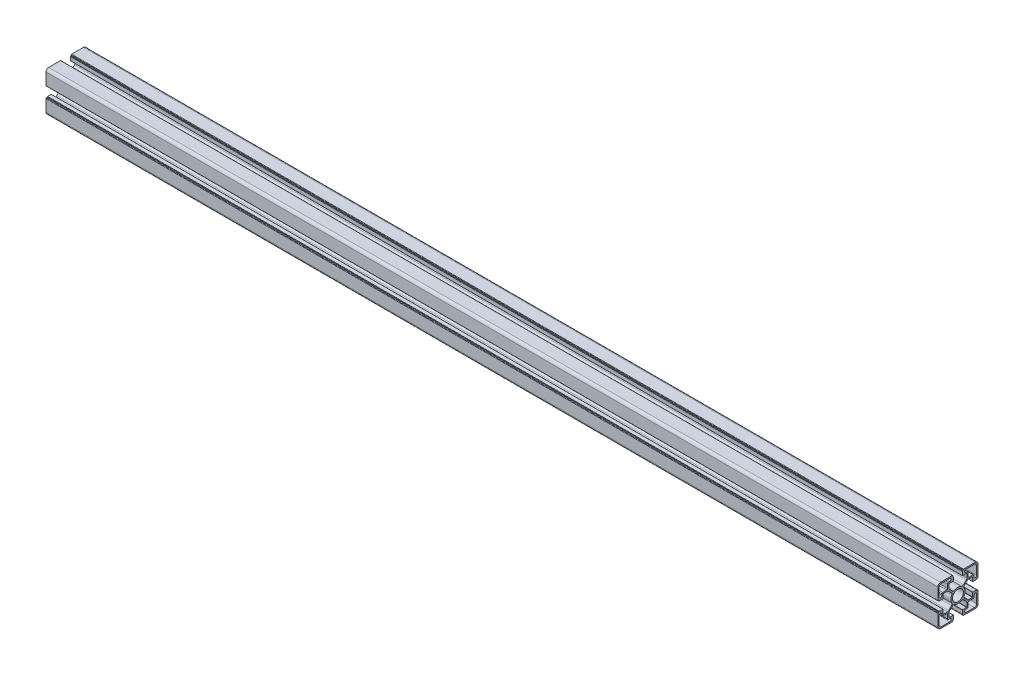
SolidWorks part; units mm, degrees
material "6061 Alloy"
ref_plane "Front Plane" through (0, 0, 0) normal (0, 0, 1) x (1, 0, 0)
ref_plane "Top Plane" through (0, 0, 0) normal (0, 1, 0) x (1, 0, 0)
ref_plane "Right Plane" through (0, 0, 0) normal (1, 0, 0) x (0, 0, -1)
sketch "Sketch1" plane through (0, 0, 0) normal (1, 0, 0) x (0, 0, -1)
  line L0 (0, 0) -> (-22.3216, 22.3216) construction
  line L1 (0, 0) -> (-31.5011, 0) construction
  line L2 (-22.5, 19.5) -> (-22.5, 6.3)
  line L3 (-20.7, 5) -> (-16.7, 5)
  line L4 (-16.5, 5.2) -> (-16.5, 9.8)
  line L5 (-16.3, 10) -> (-11.8642, 10)
  line L6 (-10.4924, 9.4318) -> (-7.2967, 6.236)
  line L7 (-21, 18.5) -> (-21, 9)
  line L8 (-16.5, 5) -> (-16.5, 10) construction
  line L9 (-18, 9) -> (-18, 10.5)
  line L10 (-17, 11.5) -> (-12.5, 11.5)
  line L11 (-22, 5.8) -> (-21.3, 5.8)
  line L12 (-21, 5.5) -> (-21, 5.3)
  line L13 (-21, 22.5) -> (-21, 6.5) construction
  line L14 (-18, 11.5) -> (-10.4393, 11.5) construction
  line L15 (-10.4393, 11.5) -> (-5.1016, 6.1623) construction
  line L16 (-18, 6.5) -> (-18, 11.5) construction
  line L17 (-22.5, 22.5) -> (-22.5, 5) construction
  line L18 (-22.5, 5) -> (-16.5, 5) construction
  line L19 (-21, 6.5) -> (-18, 6.5) construction
  line L20 (-16.5, 10) -> (-11.0607, 10) construction
  line L21 (-11.0607, 10) -> (-6.1623, 5.1016) construction
  line L22 (-5.5, 21) -> (-5.3, 21)
  line L23 (-5.8, 22) -> (-5.8, 21.3)
  line L24 (-11.5, 17) -> (-11.5, 12.5)
  line L25 (-9, 18) -> (-10.5, 18)
  line L26 (-18.5, 21) -> (-9, 21)
  line L27 (-9.4318, 10.4924) -> (-6.236, 7.2967)
  line L28 (-10, 16.3) -> (-10, 11.8642)
  line L29 (-5.2, 16.5) -> (-9.8, 16.5)
  line L30 (-5, 20.7) -> (-5, 16.7)
  line L31 (-19.5, 22.5) -> (-6.3, 22.5)
  line L32 (19.5, 22.5) -> (6.3, 22.5)
  line L33 (5, 20.7) -> (5, 16.7)
  line L34 (5.2, 16.5) -> (9.8, 16.5)
  line L35 (10, 16.3) -> (10, 11.8642)
  line L36 (9.4318, 10.4924) -> (6.236, 7.2967)
  line L37 (18.5, 21) -> (9, 21)
  line L38 (9, 18) -> (10.5, 18)
  line L39 (11.5, 17) -> (11.5, 12.5)
  line L40 (5.8, 22) -> (5.8, 21.3)
  line L41 (5.5, 21) -> (5.3, 21)
  line L42 (21, 5.5) -> (21, 5.3)
  line L43 (22, 5.8) -> (21.3, 5.8)
  line L44 (17, 11.5) -> (12.5, 11.5)
  line L45 (18, 9) -> (18, 10.5)
  line L46 (21, 18.5) -> (21, 9)
  line L47 (10.4924, 9.4318) -> (7.2967, 6.236)
  line L48 (16.3, 10) -> (11.8642, 10)
  line L49 (16.5, 5.2) -> (16.5, 9.8)
  line L50 (20.7, 5) -> (16.7, 5)
  line L51 (22.5, 19.5) -> (22.5, 6.3)
  line L52 (0, 0) -> (22.3216, 22.3216) construction
  line L53 (0, 0) -> (0, 31.5011) construction
  line L54 (22.5, -19.5) -> (22.5, -6.3)
  line L55 (20.7, -5) -> (16.7, -5)
  line L56 (16.5, -5.2) -> (16.5, -9.8)
  line L57 (16.3, -10) -> (11.8642, -10)
  line L58 (10.4924, -9.4318) -> (7.2967, -6.236)
  line L59 (21, -18.5) -> (21, -9)
  line L60 (18, -9) -> (18, -10.5)
  line L61 (17, -11.5) -> (12.5, -11.5)
  line L62 (22, -5.8) -> (21.3, -5.8)
  line L63 (21, -5.5) -> (21, -5.3)
  line L64 (5.5, -21) -> (5.3, -21)
  line L65 (5.8, -22) -> (5.8, -21.3)
  line L66 (11.5, -17) -> (11.5, -12.5)
  line L67 (9, -18) -> (10.5, -18)
  line L68 (18.5, -21) -> (9, -21)
  line L69 (9.4318, -10.4924) -> (6.236, -7.2967)
  line L70 (10, -16.3) -> (10, -11.8642)
  line L71 (5.2, -16.5) -> (9.8, -16.5)
  line L72 (5, -20.7) -> (5, -16.7)
  line L73 (19.5, -22.5) -> (6.3, -22.5)
  line L74 (0, 0) -> (22.3216, -22.3216) construction
  line L75 (0, 0) -> (31.5011, 0) construction
  line L76 (-19.5, -22.5) -> (-6.3, -22.5)
  line L77 (-5, -20.7) -> (-5, -16.7)
  line L78 (-5.2, -16.5) -> (-9.8, -16.5)
  line L79 (-10, -16.3) -> (-10, -11.8642)
  line L80 (-9.4318, -10.4924) -> (-6.236, -7.2967)
  line L81 (-18.5, -21) -> (-9, -21)
  line L82 (-9, -18) -> (-10.5, -18)
  line L83 (-11.5, -17) -> (-11.5, -12.5)
  line L84 (-5.8, -22) -> (-5.8, -21.3)
  line L85 (-5.5, -21) -> (-5.3, -21)
  line L86 (-21, -5.5) -> (-21, -5.3)
  line L87 (-22, -5.8) -> (-21.3, -5.8)
  line L88 (-17, -11.5) -> (-12.5, -11.5)
  line L89 (-18, -9) -> (-18, -10.5)
  line L90 (-21, -18.5) -> (-21, -9)
  line L91 (-10.4924, -9.4318) -> (-7.2967, -6.236)
  line L92 (-16.3, -10) -> (-11.8642, -10)
  line L93 (-16.5, -5.2) -> (-16.5, -9.8)
  line L94 (-20.7, -5) -> (-16.7, -5)
  line L95 (-22.5, -19.5) -> (-22.5, -6.3)
  line L96 (0, 0) -> (-22.3216, -22.3216) construction
  line L97 (0, 0) -> (0, -31.5011) construction
  arc A0 (0, 6.1) -> (-6.1, 0) centre (0, 0) ccw
  arc A1 (-6.9766, 3.9149) -> (-8, 0) centre (0, 0) ccw
  arc A2 (-21, 9) -> (-18, 9) centre (-19.5, 9) ccw
  arc A3 (-22, 5.8) -> (-22.5, 6.3) centre (-22, 6.3) cw
  arc A4 (-21.3, 5.8) -> (-21, 5.5) centre (-21.3, 5.5) cw
  arc A5 (-21, 5.3) -> (-20.7, 5) centre (-20.7, 5.3) ccw
  arc A6 (-16.7, 5) -> (-16.5, 5.2) centre (-16.7, 5.2) ccw
  arc A7 (-16.5, 9.8) -> (-16.3, 10) centre (-16.3, 9.8) cw
  arc A8 (-7.2967, 6.236) -> (-6.9766, 3.9149) centre (-8.6685, 4.8643) cw
  arc A9 (-11.8642, 10) -> (-10.4924, 9.4318) centre (-11.8642, 8.06) cw
  arc A10 (-18, 10.5) -> (-17, 11.5) centre (-17, 10.5) cw
  arc A11 (-10.5, 18) -> (-11.5, 17) centre (-10.5, 17) ccw
  arc A12 (-10, 11.8642) -> (-9.4318, 10.4924) centre (-8.06, 11.8642) ccw
  arc A13 (-6.236, 7.2967) -> (-3.9149, 6.9766) centre (-4.8643, 8.6685) ccw
  arc A14 (-9.8, 16.5) -> (-10, 16.3) centre (-9.8, 16.3) ccw
  arc A15 (-5, 16.7) -> (-5.2, 16.5) centre (-5.2, 16.7) cw
  arc A16 (-5.3, 21) -> (-5, 20.7) centre (-5.3, 20.7) cw
  arc A17 (-5.8, 21.3) -> (-5.5, 21) centre (-5.5, 21.3) ccw
  arc A18 (-5.8, 22) -> (-6.3, 22.5) centre (-6.3, 22) ccw
  arc A19 (-9, 21) -> (-9, 18) centre (-9, 19.5) cw
  arc A20 (-3.9149, 6.9766) -> (0, 8) centre (0, 0) cw
  arc A21 (-12.5, 11.5) -> (-11.5, 12.5) centre (-12.5, 12.5) ccw
  arc A22 (-21, 18.5) -> (-18.5, 21) centre (-18.5, 18.5) cw
  arc A23 (-22.5, 19.5) -> (-19.5, 22.5) centre (-19.5, 19.5) cw
  arc A24 (6.1, 0) -> (0, 6.1) centre (0, 0) ccw
  arc A25 (3.9149, 6.9766) -> (0, 8) centre (0, 0) ccw
  arc A26 (9, 21) -> (9, 18) centre (9, 19.5) ccw
  arc A27 (5.8, 22) -> (6.3, 22.5) centre (6.3, 22) cw
  arc A28 (5.8, 21.3) -> (5.5, 21) centre (5.5, 21.3) cw
  arc A29 (5.3, 21) -> (5, 20.7) centre (5.3, 20.7) ccw
  arc A30 (5, 16.7) -> (5.2, 16.5) centre (5.2, 16.7) ccw
  arc A31 (9.8, 16.5) -> (10, 16.3) centre (9.8, 16.3) cw
  arc A32 (6.236, 7.2967) -> (3.9149, 6.9766) centre (4.8643, 8.6685) cw
  arc A33 (10, 11.8642) -> (9.4318, 10.4924) centre (8.06, 11.8642) cw
  arc A34 (10.5, 18) -> (11.5, 17) centre (10.5, 17) cw
  arc A35 (18, 10.5) -> (17, 11.5) centre (17, 10.5) ccw
  arc A36 (11.8642, 10) -> (10.4924, 9.4318) centre (11.8642, 8.06) ccw
  arc A37 (7.2967, 6.236) -> (6.9766, 3.9149) centre (8.6685, 4.8643) ccw
  arc A38 (16.5, 9.8) -> (16.3, 10) centre (16.3, 9.8) ccw
  arc A39 (16.7, 5) -> (16.5, 5.2) centre (16.7, 5.2) cw
  arc A40 (21, 5.3) -> (20.7, 5) centre (20.7, 5.3) cw
  arc A41 (21.3, 5.8) -> (21, 5.5) centre (21.3, 5.5) ccw
  arc A42 (22, 5.8) -> (22.5, 6.3) centre (22, 6.3) ccw
  arc A43 (21, 9) -> (18, 9) centre (19.5, 9) cw
  arc A44 (6.9766, 3.9149) -> (8, 0) centre (0, 0) cw
  arc A45 (11.5, 12.5) -> (12.5, 11.5) centre (12.5, 12.5) ccw
  arc A46 (18.5, 21) -> (21, 18.5) centre (18.5, 18.5) cw
  arc A47 (19.5, 22.5) -> (22.5, 19.5) centre (19.5, 19.5) cw
  arc A48 (0, -6.1) -> (6.1, 0) centre (0, 0) ccw
  arc A49 (6.9766, -3.9149) -> (8, 0) centre (0, 0) ccw
  arc A50 (21, -9) -> (18, -9) centre (19.5, -9) ccw
  arc A51 (22, -5.8) -> (22.5, -6.3) centre (22, -6.3) cw
  arc A52 (21.3, -5.8) -> (21, -5.5) centre (21.3, -5.5) cw
  arc A53 (21, -5.3) -> (20.7, -5) centre (20.7, -5.3) ccw
  arc A54 (16.7, -5) -> (16.5, -5.2) centre (16.7, -5.2) ccw
  arc A55 (16.5, -9.8) -> (16.3, -10) centre (16.3, -9.8) cw
  arc A56 (7.2967, -6.236) -> (6.9766, -3.9149) centre (8.6685, -4.8643) cw
  arc A57 (11.8642, -10) -> (10.4924, -9.4318) centre (11.8642, -8.06) cw
  arc A58 (18, -10.5) -> (17, -11.5) centre (17, -10.5) cw
  arc A59 (10.5, -18) -> (11.5, -17) centre (10.5, -17) ccw
  arc A60 (10, -11.8642) -> (9.4318, -10.4924) centre (8.06, -11.8642) ccw
  arc A61 (6.236, -7.2967) -> (3.9149, -6.9766) centre (4.8643, -8.6685) ccw
  arc A62 (9.8, -16.5) -> (10, -16.3) centre (9.8, -16.3) ccw
  arc A63 (5, -16.7) -> (5.2, -16.5) centre (5.2, -16.7) cw
  arc A64 (5.3, -21) -> (5, -20.7) centre (5.3, -20.7) cw
  arc A65 (5.8, -21.3) -> (5.5, -21) centre (5.5, -21.3) ccw
  arc A66 (5.8, -22) -> (6.3, -22.5) centre (6.3, -22) ccw
  arc A67 (9, -21) -> (9, -18) centre (9, -19.5) cw
  arc A68 (3.9149, -6.9766) -> (0, -8) centre (0, 0) cw
  arc A69 (12.5, -11.5) -> (11.5, -12.5) centre (12.5, -12.5) ccw
  arc A70 (21, -18.5) -> (18.5, -21) centre (18.5, -18.5) cw
  arc A71 (22.5, -19.5) -> (19.5, -22.5) centre (19.5, -19.5) cw
  arc A72 (-6.1, 0) -> (0, -6.1) centre (0, 0) ccw
  arc A73 (-3.9149, -6.9766) -> (0, -8) centre (0, 0) ccw
  arc A74 (-9, -21) -> (-9, -18) centre (-9, -19.5) ccw
  arc A75 (-5.8, -22) -> (-6.3, -22.5) centre (-6.3, -22) cw
  arc A76 (-5.8, -21.3) -> (-5.5, -21) centre (-5.5, -21.3) cw
  arc A77 (-5.3, -21) -> (-5, -20.7) centre (-5.3, -20.7) ccw
  arc A78 (-5, -16.7) -> (-5.2, -16.5) centre (-5.2, -16.7) ccw
  arc A79 (-9.8, -16.5) -> (-10, -16.3) centre (-9.8, -16.3) cw
  arc A80 (-6.236, -7.2967) -> (-3.9149, -6.9766) centre (-4.8643, -8.6685) cw
  arc A81 (-10, -11.8642) -> (-9.4318, -10.4924) centre (-8.06, -11.8642) cw
  arc A82 (-10.5, -18) -> (-11.5, -17) centre (-10.5, -17) cw
  arc A83 (-18, -10.5) -> (-17, -11.5) centre (-17, -10.5) ccw
  arc A84 (-11.8642, -10) -> (-10.4924, -9.4318) centre (-11.8642, -8.06) ccw
  arc A85 (-7.2967, -6.236) -> (-6.9766, -3.9149) centre (-8.6685, -4.8643) ccw
  arc A86 (-16.5, -9.8) -> (-16.3, -10) centre (-16.3, -9.8) ccw
  arc A87 (-16.7, -5) -> (-16.5, -5.2) centre (-16.7, -5.2) cw
  arc A88 (-21, -5.3) -> (-20.7, -5) centre (-20.7, -5.3) cw
  arc A89 (-21.3, -5.8) -> (-21, -5.5) centre (-21.3, -5.5) ccw
  arc A90 (-22, -5.8) -> (-22.5, -6.3) centre (-22, -6.3) ccw
  arc A91 (-21, -9) -> (-18, -9) centre (-19.5, -9) cw
  arc A92 (-6.9766, -3.9149) -> (-8, 0) centre (0, 0) cw
  arc A93 (-11.5, -12.5) -> (-12.5, -11.5) centre (-12.5, -12.5) ccw
  arc A94 (-18.5, -21) -> (-21, -18.5) centre (-18.5, -18.5) cw
  arc A95 (-19.5, -22.5) -> (-22.5, -19.5) centre (-19.5, -19.5) cw
  point P8 (-16.5, 7.5)
  point P79 (-11.5, 11.5)
  point P82 (-21, 21)
  point P296 (0, 0)
  dimension "D1" = 12.2
  dimension "D2" = 16
  dimension "D12" = 0.5
  dimension "D13" = 0.3
  dimension "D14" = 0.3
  dimension "D15" = 0.2
  dimension "D16" = 0.2
  dimension "D6" = 1.94
  dimension "D17" = 1
  dimension "D18" = 1
  dimension "D19" = 2.5
  dimension "D4" = 3
  dimension "D3" = 45
  dimension "D5" = 0.8
  dimension "D7" = 6
  dimension "D8" = 1.5
  dimension "D10" = 1.5
  dimension "D11" = 4
  dimension "D9" = 1.5
  dimension "D20" = 4
extrude "Boss-Extrude2" add sketch "Sketch1" along normal mid plane 1000 contours A95 L76 A75 L84 A76 L85 A77 L77 A78 L78 A79 L79 A81 L80 A80 A73 A68 A61 L69 A60 L70 A62 L71 A63 L72 A64 L64 A65 L65 A66 L73 A71 L54 A51 L62 A52 L63 A53 L55 A54 L56 A55 L57 A57 L58 A56 A49 A44 A37 L47 A36
